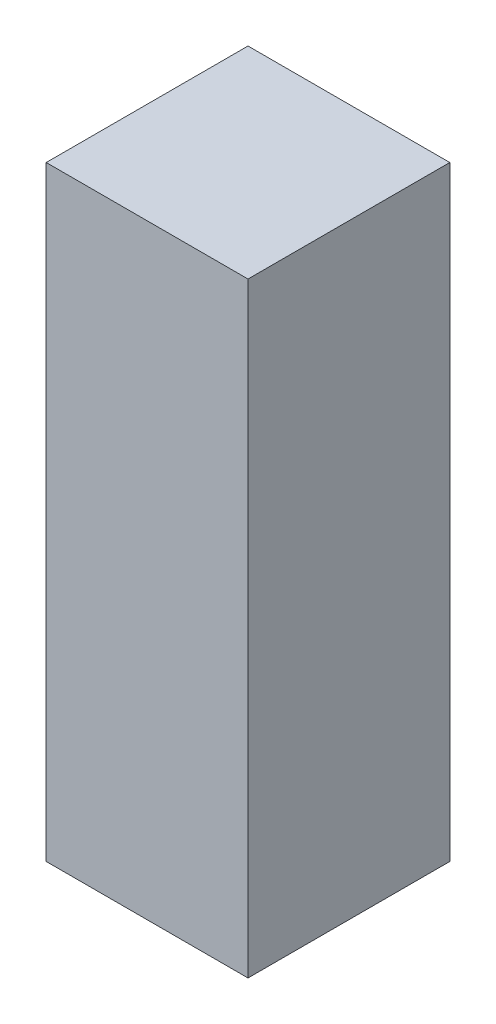
SolidWorks part; units mm, degrees
ref_plane "Front Plane" through (0, 0, 0) normal (0, 0, 1) x (1, 0, 0)
ref_plane "Top Plane" through (0, 0, 0) normal (0, 1, 0) x (1, 0, 0)
ref_plane "Right Plane" through (0, 0, 0) normal (1, 0, 0) x (0, 0, -1)
sketch "Sketch1" plane through (0, 0, 0) normal (0, 1, 0) x (1, 0, 0)
  line L1 (-0.914, 1.1305) -> (2.261, 1.1305)
  line L2 (-0.914, 1.1305) -> (-0.914, -2.0445)
  line L3 (-0.914, -2.0445) -> (2.261, -2.0445)
  line L4 (2.261, 1.1305) -> (2.261, -2.0445)
  dimension "D1" = 3.175
  dimension "D2" = 3.175
extrude "Boss-Extrude1" add sketch "Sketch1" along normal blind 9.525
